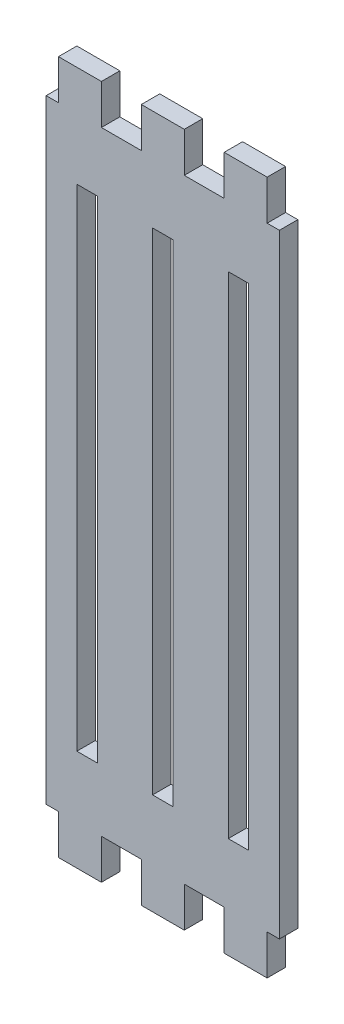
SolidWorks part; units mm, degrees
ref_plane "前视基准面" through (0, 0, 0) normal (0, 0, 1) x (1, 0, 0)
ref_plane "上视基准面" through (0, 0, 0) normal (0, 1, 0) x (1, 0, 0)
ref_plane "右视基准面" through (0, 0, 0) normal (1, 0, 0) x (0, 0, -1)
sketch "草图1" plane through (0, 0, 0) normal (0, 0, 1) x (1, 0, 0)
  line L0 (-17, 50) -> (-10, 50)
  line L1 (-19, 50) -> (19, 50)
  line L2 (-19, 50) -> (-19, -50)
  line L3 (-19, -50) -> (19, -50)
  line L4 (19, 50) -> (19, -50)
  line L5 (0, -50) -> (0, 50) construction
  line L6 (-19, 0) -> (19, 0) construction
  line L7 (-17, 50) -> (-17, 56.5)
  line L8 (-10, 50) -> (-10, 56.5)
  line L9 (-17, 56.5) -> (-10, 56.5)
  line L10 (-3.5, 50) -> (3.5, 50)
  line L11 (-3.5, 50) -> (-3.5, 56.5)
  line L12 (3.5, 50) -> (3.5, 56.5)
  line L13 (-3.5, 56.5) -> (3.5, 56.5)
  line L14 (10, 50) -> (17, 50)
  line L15 (10, 50) -> (10, 56.5)
  line L16 (17, 50) -> (17, 56.5)
  line L17 (10, 56.5) -> (17, 56.5)
  line L18 (10, -56.5) -> (17, -56.5)
  line L19 (17, -50) -> (17, -56.5)
  line L20 (10, -50) -> (10, -56.5)
  line L21 (10, -50) -> (17, -50)
  line L22 (-3.5, -56.5) -> (3.5, -56.5)
  line L23 (3.5, -50) -> (3.5, -56.5)
  line L24 (-3.5, -50) -> (-3.5, -56.5)
  line L25 (-3.5, -50) -> (3.5, -50)
  line L26 (-17, -56.5) -> (-10, -56.5)
  line L27 (-10, -50) -> (-10, -56.5)
  line L28 (-17, -50) -> (-17, -56.5)
  line L29 (-17, -50) -> (-10, -50)
  line L31 (-1.6667, 40) -> (1.6667, 40)
  line L32 (-1.6667, 40) -> (-1.6667, -40)
  line L33 (-1.6667, -40) -> (1.6667, -40)
  line L34 (1.6667, 40) -> (1.6667, -40)
  line L35 (0, -40) -> (0, 40) construction
  line L36 (-1.6667, 0) -> (1.6667, 0) construction
  line L37 (-14, 40) -> (-10.6667, 40)
  line L38 (-14, 40) -> (-14, -40)
  line L39 (-14, -40) -> (-10.6667, -40)
  line L40 (-10.6667, 40) -> (-10.6667, -40)
  line L41 (-12.3333, -40) -> (-12.3333, 40) construction
  line L42 (-14, 0) -> (-10.6667, 0) construction
  line L43 (10.6667, 40) -> (14, 40)
  line L44 (10.6667, 40) -> (10.6667, -40)
  line L45 (10.6667, -40) -> (14, -40)
  line L46 (14, 40) -> (14, -40)
  line L47 (12.3333, -40) -> (12.3333, 40) construction
  line L48 (10.6667, 0) -> (14, 0) construction
  point P0 (0, 0)
  point P28 (0, 0)
  point P32 (-12.3333, 0)
  point P36 (12.3333, 0)
  dimension "D1" = 6.5
  dimension "D2" = 6.5
  dimension "D3" = 6.5
  dimension "D4" = 2
  dimension "D5" = 2
  dimension "D6" = 7
  dimension "D7" = 100
  dimension "D8" = 9
  dimension "D9" = 9
  dimension "D10" = 5
  dimension "D11" = 10
extrude "凸台-拉伸1" add sketch "草图1" along normal blind 3 contours L3 L24 L22 L23 | L3 L28 L26 L27 | L3 L20 L18 L19 | L4 L1 L0 L2 L3 L31 L34 L33 L32 L37 L40 L39 L38 L43 L46 L45 L44 | L13 L12 L10 L11 | L17 L16 L14 L15
